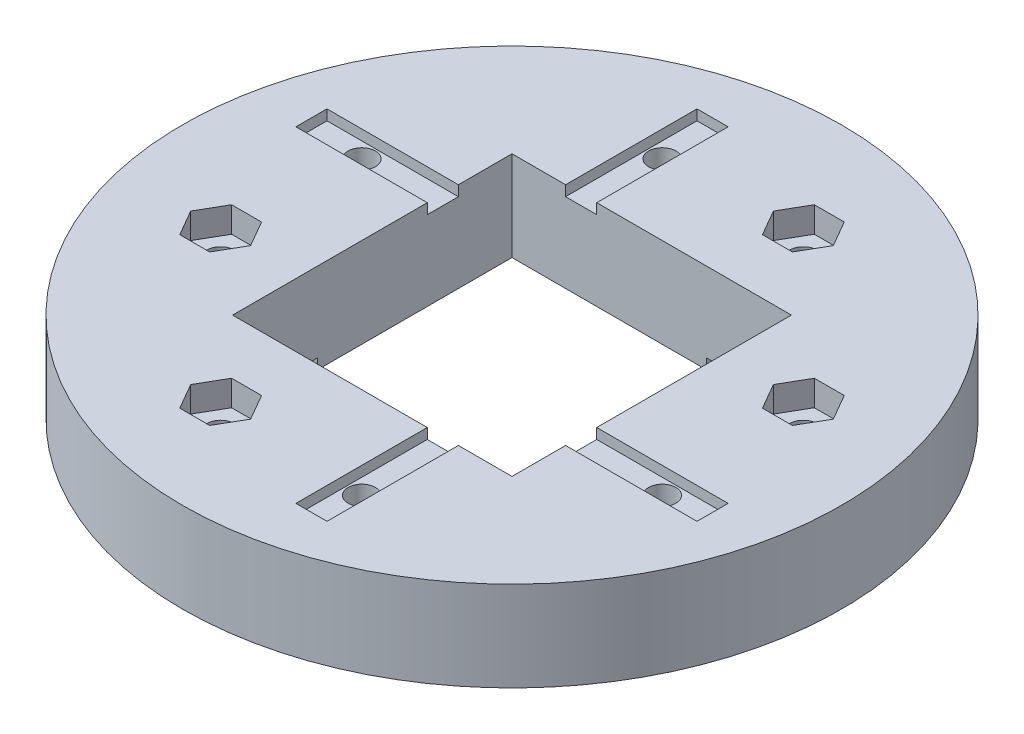
SolidWorks part; units mm, degrees
material "PLA"
ref_plane "Front Plane" through (0, 0, 0) normal (0, 0, 1) x (1, 0, 0)
ref_plane "Top Plane" through (0, 0, 0) normal (0, 1, 0) x (1, 0, 0)
ref_plane "Right Plane" through (0, 0, 0) normal (1, 0, 0) x (0, 0, -1)
sketch "Sketch1" plane through (0, 0, 0) normal (0, 1, 0) x (1, 0, 0)
  line L1 (-20.2, -20.2) -> (20.2, -20.2)
  line L2 (-20.2, -20.2) -> (-20.2, 20.2)
  line L3 (-20.2, 20.2) -> (20.2, 20.2)
  line L4 (20.2, -20.2) -> (20.2, 20.2)
  line L5 (-20.2, -20.2) -> (20.2, 20.2) construction
  line L6 (-20.2, 20.2) -> (20.2, -20.2) construction
  circle A0 centre (0, 0) radius 50.1
  point P0 (0, 0)
  dimension "D3" = 100.2
  dimension "D1" = 40.4
  dimension "D2" = 40.4
extrude "Boss-Extrude1" add sketch "Sketch1" along normal blind 13
sketch "Sketch3" plane through (0, 13, 0) normal (0, 1, 0) x (1, 0, 0)
  line L0 (20.2, 20.2) -> (-20.2, 20.2) construction
  line L1 (-20.2, 20.2) -> (-10.2, 20.2) construction
  line L2 (-18.7, 20.2) -> (-1.7, 20.2)
  line L4 (-18.7, 20.2) -> (-1.7, 20.2)
  line L5 (-18.7, 20.2) -> (-18.7, 40.2)
  line L6 (-18.7, 40.2) -> (-1.7, 40.2)
  line L7 (-1.7, 20.2) -> (-1.7, 40.2)
  circle A0 centre (0, 0) radius 50.1 construction
  point P0 (0, 20.2)
  point P1 (0, 50.1)
  point P4 (-20.2, 20.2)
  point P7 (-25.3005, 43.2423)
  point P9 (20.2, 20.2)
  point P10 (25.3005, 43.2423)
  point P17 (-10.2, 20.2)
  point P19 (-20.8193, 45.5693)
  dimension "D1" = 10
  dimension "D2" = 17
  dimension "D3" = 20
sketch "Sketch4" plane through (0, 13, 0) normal (0, 1, 0) x (1, 0, 0)
  line L0 (-18.7, 20.2) -> (-1.7, 20.2) construction
  line L1 (-12.45, 20.2) -> (-7.95, 20.2)
  line L2 (-12.45, 20.2) -> (-12.45, 39.2)
  line L3 (-12.45, 39.2) -> (-7.95, 39.2)
  line L4 (-7.95, 20.2) -> (-7.95, 39.2)
  line L5 (0, 20.2) -> (0, 29.2596) construction
  line L14 (39.2, -12.45) -> (39.2, -7.95)
  line L15 (20.2, -7.95) -> (39.2, -7.95)
  line L16 (20.2, -12.45) -> (20.2, -7.95)
  line L17 (20.2, -12.45) -> (39.2, -12.45)
  line L18 (12.45, -20.2) -> (12.45, -39.2)
  line L19 (12.45, -20.2) -> (7.95, -20.2)
  line L20 (7.95, -20.2) -> (7.95, -39.2)
  line L21 (12.45, -39.2) -> (7.95, -39.2)
  line L30 (-39.2, 12.45) -> (-39.2, 7.95)
  line L31 (-20.2, 7.95) -> (-39.2, 7.95)
  line L32 (-20.2, 12.45) -> (-20.2, 7.95)
  line L33 (-20.2, 12.45) -> (-39.2, 12.45)
  line L34 (20.2, 12.45) -> (39.2, 12.45) [skipped]
  line L35 (39.2, 12.45) -> (39.2, 7.95) [skipped]
  line L36 (20.2, 7.95) -> (39.2, 7.95) [skipped]
  line L37 (20.2, 12.45) -> (20.2, 7.95) [skipped]
  line L38 (-20.2, -12.45) -> (-39.2, -12.45) [skipped]
  line L39 (-39.2, -12.45) -> (-39.2, -7.95) [skipped]
  line L40 (-20.2, -7.95) -> (-39.2, -7.95) [skipped]
  line L41 (-20.2, -12.45) -> (-20.2, -7.95) [skipped]
  point P6 (-10.2, 20.2)
  point P45 (0, 0)
  dimension "D1" = 4.5
  dimension "D2" = 0
  dimension "D3" = 19
  dimension "D4" = 4
extrude "Cut-Extrude1" cut sketch "Sketch4" against normal blind 1.5
sketch "Sketch5" plane through (0, 0, 0) normal (0, -1, 0) x (1, 0, 0)
  line L0 (-20.2, 20.2) -> (20.2, 20.2) construction
  line L1 (-12.45, 20.2) -> (-7.95, 20.2)
  line L2 (-12.45, 20.2) -> (-12.45, 39.2)
  line L3 (-12.45, 39.2) -> (-7.95, 39.2)
  line L4 (-7.95, 20.2) -> (-7.95, 39.2)
  line L5 (-20.2, -20.2) -> (-20.2, 20.2) construction
  line L6 (0, 20.2) -> (0, 33.0635) construction
  line L15 (39.2, -12.45) -> (39.2, -7.95)
  line L16 (20.2, -7.95) -> (39.2, -7.95)
  line L17 (20.2, -12.45) -> (20.2, -7.95)
  line L18 (20.2, -12.45) -> (39.2, -12.45)
  line L19 (12.45, -20.2) -> (12.45, -39.2)
  line L20 (12.45, -20.2) -> (7.95, -20.2)
  line L21 (7.95, -20.2) -> (7.95, -39.2)
  line L22 (12.45, -39.2) -> (7.95, -39.2)
  line L31 (-39.2, 12.45) -> (-39.2, 7.95)
  line L32 (-20.2, 7.95) -> (-39.2, 7.95)
  line L33 (-20.2, 12.45) -> (-20.2, 7.95)
  line L34 (-20.2, 12.45) -> (-39.2, 12.45)
  line L35 (20.2, 12.45) -> (39.2, 12.45) [skipped]
  line L36 (39.2, 12.45) -> (39.2, 7.95) [skipped]
  line L37 (20.2, 7.95) -> (39.2, 7.95) [skipped]
  line L38 (20.2, 12.45) -> (20.2, 7.95) [skipped]
  line L39 (-20.2, -12.45) -> (-39.2, -12.45) [skipped]
  line L40 (-39.2, -12.45) -> (-39.2, -7.95) [skipped]
  line L41 (-20.2, -7.95) -> (-39.2, -7.95) [skipped]
  line L42 (-20.2, -12.45) -> (-20.2, -7.95) [skipped]
  point P6 (-10.2, 20.2)
  point P44 (0, 0)
  dimension "D1" = 10
  dimension "D2" = 4.5
  dimension "D3" = 19
  dimension "D4" = 4
extrude "Cut-Extrude2" cut sketch "Sketch5" against normal blind 1.5
sketch "Sketch6" plane through (0, 13, 0) normal (0, 1, 0) x (1, 0, 0)
  line L0 (20.2, -7.95) -> (20.2, -12.45) construction
  line L1 (-18.7, 20.2) -> (-1.7, 20.2) construction
  line L2 (-20.2, 7.95) -> (-20.2, 12.45) construction
  line L3 (12.45, -20.2) -> (20.2, -20.2) construction
  circle A0 centre (31.925, -10.2) radius 1.975
  circle A1 centre (-10.2, 31.925) radius 1.975
  circle A2 centre (-31.925, 10.2) radius 1.975
  circle A3 centre (10.2, -31.925) radius 1.975
  point P0 (33.9, -10.2)
  point P5 (33.9, -10.2)
  point P6 (10.2, -33.9)
  point P7 (-33.9, 10.2)
  point P8 (-10.2, 33.9)
  point P21 (-10.2, 33.9)
  point P22 (10.2, -33.9)
  point P23 (-33.9, 10.2)
  dimension "D2" = 3.95
  dimension "D6" = 3.95
  dimension "D7" = 3.95
  dimension "D8" = 3.95
  dimension "D1" = 13.7
  dimension "D3" = 13.7
  dimension "D4" = 13.7
  dimension "D5" = 13.7
extrude "Cut-Extrude3" cut sketch "Sketch6" against normal blind 21.5
sketch "Sketch8" plane through (0, 0, 0) normal (0, -1, 0) x (1, 0, 0)
  line L0 (-12.45, 20.2) -> (-7.95, 20.2) construction
  line L1 (20.2, -7.95) -> (20.2, -12.45) construction
  line L2 (20.2, -20.2) -> (12.45, -20.2) construction
  line L3 (-20.2, 7.95) -> (-20.2, 12.45) construction
  circle A0 centre (-10.2, 31.925) radius 1.975
  circle A1 centre (31.925, -10.2) radius 1.975
  circle A2 centre (10.2, -31.925) radius 1.975
  circle A3 centre (-31.925, 10.2) radius 1.975
  point P0 (-10.2, 33.9)
  point P1 (-33.9, 10.2)
  point P2 (10.2, -33.9)
  point P3 (33.9, -10.2)
  point P20 (-10.2, 33.9)
  point P21 (-33.9, 10.2)
  point P22 (10.2, -33.9)
  point P23 (33.9, -10.2)
  dimension "D5" = 3.95
  dimension "D6" = 3.95
  dimension "D7" = 3.95
  dimension "D8" = 3.95
  dimension "D1" = 13.7
  dimension "D2" = 13.7
  dimension "D3" = 13.7
  dimension "D4" = 13.7
extrude "Cut-Extrude4" cut sketch "Sketch8" against normal blind 21.5
sketch "Sketch9" plane through (0, 0, 0) normal (0, -1, 0) x (1, 0, 0)
  line L1 (14.5301, 31.925) -> (12.3651, 35.675)
  line L2 (12.3651, 35.675) -> (8.0349, 35.675)
  line L3 (8.0349, 35.675) -> (5.8699, 31.925)
  line L4 (5.8699, 31.925) -> (8.0349, 28.175)
  line L5 (8.0349, 28.175) -> (12.3651, 28.175)
  line L6 (12.3651, 28.175) -> (14.5301, 31.925)
  line L7 (36.2551, 10.2) -> (34.0901, 13.95)
  line L8 (34.0901, 13.95) -> (29.7599, 13.95)
  line L9 (29.7599, 13.95) -> (27.5949, 10.2)
  line L10 (27.5949, 10.2) -> (29.7599, 6.45)
  line L11 (29.7599, 6.45) -> (34.0901, 6.45)
  line L12 (34.0901, 6.45) -> (36.2551, 10.2)
  line L13 (-27.5949, -10.2) -> (-29.7599, -6.45)
  line L14 (-29.7599, -6.45) -> (-34.0901, -6.45)
  line L15 (-34.0901, -6.45) -> (-36.2551, -10.2)
  line L16 (-36.2551, -10.2) -> (-34.0901, -13.95)
  line L17 (-34.0901, -13.95) -> (-29.7599, -13.95)
  line L18 (-29.7599, -13.95) -> (-27.5949, -10.2)
  line L19 (-5.8699, -31.925) -> (-8.0349, -28.175)
  line L20 (-8.0349, -28.175) -> (-12.3651, -28.175)
  line L21 (-12.3651, -28.175) -> (-14.5301, -31.925)
  line L22 (-14.5301, -31.925) -> (-12.3651, -35.675)
  line L23 (-12.3651, -35.675) -> (-8.0349, -35.675)
  line L24 (-8.0349, -35.675) -> (-5.8699, -31.925)
  circle A0 centre (10.2, 31.925) radius 3.75 construction
  circle A1 centre (31.925, 10.2) radius 3.75 construction
  circle A2 centre (-31.925, -10.2) radius 3.75 construction
  circle A3 centre (-10.2, -31.925) radius 3.75 construction
  dimension "D1" = 7.5
  dimension "D2" = 7.5
  dimension "D3" = 7.5
  dimension "D4" = 7.5
extrude "Cut-Extrude5" cut sketch "Sketch9" against normal blind 3.7
sketch "Sketch10" plane through (0, 13, 0) normal (0, 1, 0) x (1, 0, 0)
  line L1 (14.5301, 31.925) -> (12.3651, 35.675)
  line L2 (12.3651, 35.675) -> (8.0349, 35.675)
  line L3 (8.0349, 35.675) -> (5.8699, 31.925)
  line L4 (5.8699, 31.925) -> (8.0349, 28.175)
  line L5 (8.0349, 28.175) -> (12.3651, 28.175)
  line L6 (12.3651, 28.175) -> (14.5301, 31.925)
  line L7 (36.2551, 10.2) -> (34.0901, 13.95)
  line L8 (34.0901, 13.95) -> (29.7599, 13.95)
  line L9 (29.7599, 13.95) -> (27.5949, 10.2)
  line L10 (27.5949, 10.2) -> (29.7599, 6.45)
  line L11 (29.7599, 6.45) -> (34.0901, 6.45)
  line L12 (34.0901, 6.45) -> (36.2551, 10.2)
  line L13 (-5.8699, -31.925) -> (-8.0349, -28.175)
  line L14 (-8.0349, -28.175) -> (-12.3651, -28.175)
  line L15 (-12.3651, -28.175) -> (-14.5301, -31.925)
  line L16 (-14.5301, -31.925) -> (-12.3651, -35.675)
  line L17 (-12.3651, -35.675) -> (-8.0349, -35.675)
  line L18 (-8.0349, -35.675) -> (-5.8699, -31.925)
  line L19 (-27.5949, -10.2) -> (-29.7599, -6.45)
  line L20 (-29.7599, -6.45) -> (-34.0901, -6.45)
  line L21 (-34.0901, -6.45) -> (-36.2551, -10.2)
  line L22 (-36.2551, -10.2) -> (-34.0901, -13.95)
  line L23 (-34.0901, -13.95) -> (-29.7599, -13.95)
  line L24 (-29.7599, -13.95) -> (-27.5949, -10.2)
  circle A0 centre (10.2, 31.925) radius 3.75 construction
  circle A1 centre (31.925, 10.2) radius 3.75 construction
  circle A2 centre (-10.2, -31.925) radius 3.75 construction
  circle A3 centre (-31.925, -10.2) radius 3.75 construction
  dimension "D1" = 7.5
  dimension "D2" = 7.5
  dimension "D3" = 7.5
  dimension "7.5" = 7.5
extrude "Cut-Extrude6" cut sketch "Sketch10" against normal blind 3.7
sketch "Sketch11" plane through (0, 13, 0) normal (0, 1, 0) x (1, 0, 0)
  circle A0 centre (0, 0) radius 47.6
  circle A1 centre (0, 0) radius 50.1
  dimension "D1" = 95.2
extrude "Cut-Extrude7" cut sketch "Sketch11" against normal blind 24
sketch "Sketch12" plane through (0, 0, 0) normal (0, -1, 0) x (1, 0, 0)
  circle A0 centre (0, 0) radius 47.6
  circle A1 centre (0, 0) radius 47.65
  dimension "D1" = 95.3
extrude "Boss-Extrude2" add sketch "Sketch12" against normal up to surface (13 mm away) up to face at (0, 13, 0)
